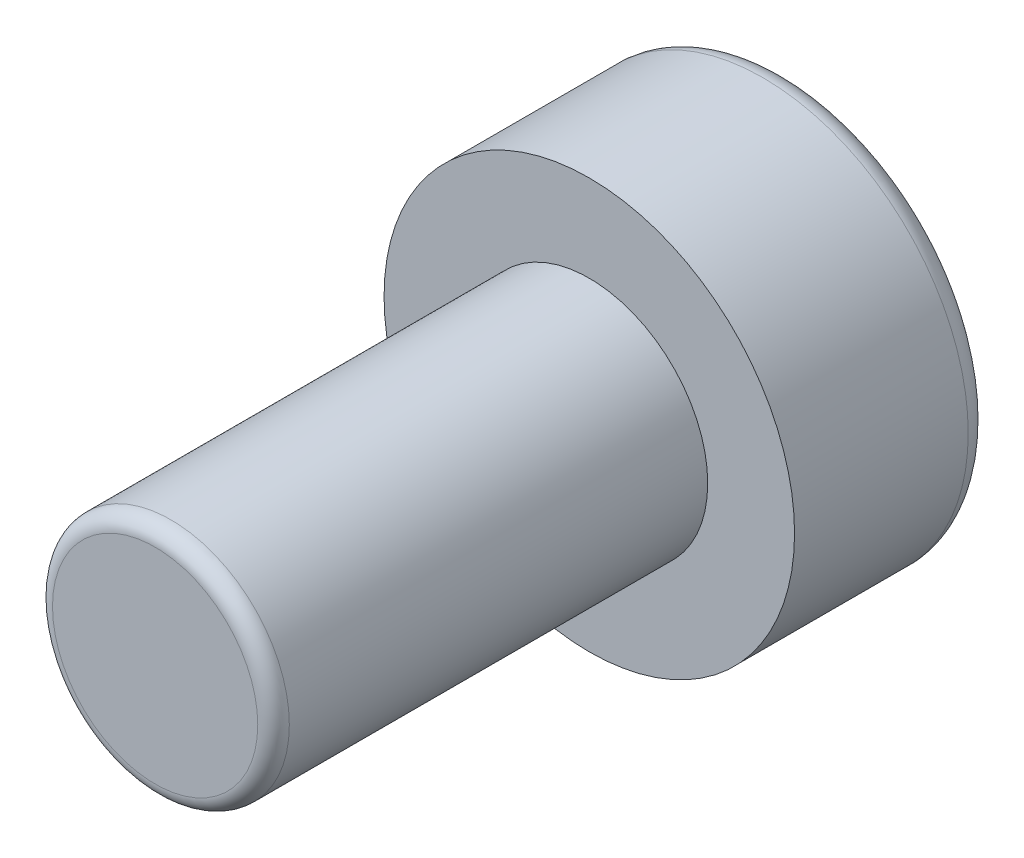
SolidWorks part; units mm, degrees
ref_plane "Front Plane" through (0, 0, 0) normal (0, 0, 1) x (1, 0, 0)
ref_plane "Top Plane" through (0, 0, 0) normal (0, 1, 0) x (1, 0, 0)
ref_plane "Right Plane" through (0, 0, 0) normal (1, 0, 0) x (0, 0, -1)
sketch "Sketch1" plane through (0, 0, 0) normal (0, 0, 1) x (1, 0, 0)
  circle A0 centre (0, 0) radius 2.6
  dimension "D1" = 5.2
extrude "Boss-Extrude1" add sketch "Sketch1" along normal blind 2.5
fillet "Fillet1" radius 0.3 1 edges at (2.6, 0, 0)
sketch "Sketch2" plane through (0, 0, 2.5) normal (0, 0, 1) x (1, 0, 0)
  circle A0 centre (0, 0) radius 1.5
  dimension "D1" = 3
extrude "Boss-Extrude2" add sketch "Sketch2" along normal blind 5.5
fillet "Fillet2" radius 0.2 1 edges at (1.5, 0, 8)
